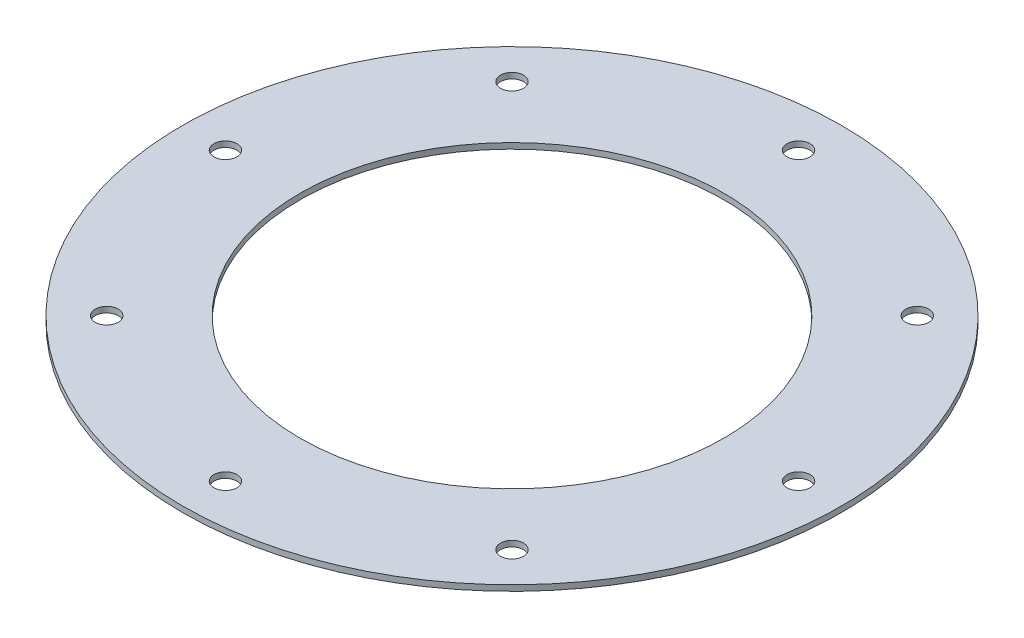
SolidWorks part; units mm, degrees
ref_plane "Front Plane" through (0, 0, 0) normal (0, 0, 1) x (1, 0, 0)
ref_plane "Top Plane" through (0, 0, 0) normal (0, 1, 0) x (1, 0, 0)
ref_plane "Right Plane" through (0, 0, 0) normal (1, 0, 0) x (0, 0, -1)
sketch "Sketch1" plane through (0, 0, 0) normal (0, 1, 0) x (1, 0, 0)
  line L0 (0, 0) -> (-131.934, 0) construction
  circle A0 centre (0, 0) radius 115
  circle A1 centre (0, 0) radius 74
  circle A2 centre (-100, 0) radius 4
  circle A3 centre (-70.7107, 70.7107) radius 4
  circle A4 centre (0, 100) radius 4
  circle A5 centre (70.7107, 70.7107) radius 4
  circle A6 centre (100, 0) radius 4
  circle A7 centre (70.7107, -70.7107) radius 4
  circle A8 centre (0, -100) radius 4
  circle A9 centre (-70.7107, -70.7107) radius 4
  point P7 (-88.3203, 84.6268)
  point P8 (0, 0)
  point P24 (0, 0)
  dimension "D1" = 148
  dimension "D2" = 230
  dimension "D3" = 8
  dimension "D4" = 100
  dimension "D5" = 8
extrude "Boss-Extrude1" add sketch "Sketch1" along normal blind 2
